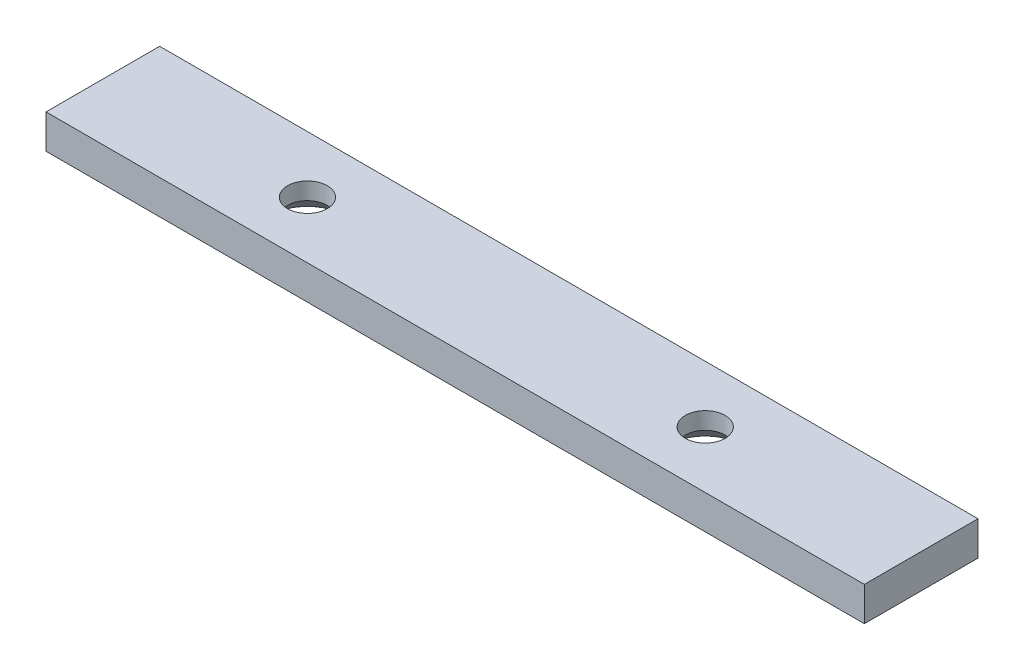
SolidWorks part; units mm, degrees
ref_plane "Front Plane" through (0, 0, 0) normal (0, 0, 1) x (1, 0, 0)
ref_plane "Top Plane" through (0, 0, 0) normal (0, 1, 0) x (1, 0, 0)
ref_plane "Right Plane" through (0, 0, 0) normal (1, 0, 0) x (0, 0, -1)
sketch "Sketch2" plane through (0, 0, 0) normal (0, 1, 0) x (1, 0, 0)
  line L1 (-72, 10) -> (72, 10)
  line L2 (-72, 10) -> (-72, -10)
  line L3 (-72, -10) -> (72, -10)
  line L4 (72, 10) -> (72, -10)
  line L5 (-72, 10) -> (72, -10) construction
  line L6 (-72, -10) -> (72, 10) construction
  point P0 (0, 0)
  dimension "D1" = 20
  dimension "D2" = 144
extrude "Boss-Extrude1" add sketch "Sketch2" along normal blind 6
hole_wizard "CSK for M2 Flat Head Machine Screw1" positions "3DSketch1" profile "Sketch3" countersink size "M2" standard "ANSI Metric" end condition up to next
sketch3d "3DSketch1"
  line L0 (72, 0, 10) -> (72, 0, -10) construction
  line L1 (-72, 0, 10) -> (72, 0, 10) construction
  point P0 (34, 0, 0)
  dimension "D1" = 38
  dimension "D2" = 10
sketch "Sketch3" plane through (34, 0, 0) normal (1, 0, 0) x (0, 0, -1)
  line L0 (0, 0) -> (0, 6)
  line L1 (0, 6) -> (3.5, 6)
  line L2 (3.5, 6) -> (3.5, 3)
  line L3 (3.5, 3) -> (6.5, 0)
  line L5 (6.5, 0) -> (0, 0)
  line L6 (-3.5, 3) -> (-6.5, 0) construction
  line L11 (0, -6.35) -> (0, 107.95) construction
  dimension "Thru Hole Dia." = 7
  dimension "Thru Hole Depth" = 6
  dimension "Near C'Sink Dia." = 13
  dimension "Near C'Sink Angle" = 90
pattern_linear "LPattern1" count 2 spacing 70 along (-1, 0, 0) of "CSK for M2 Flat Head Machine Screw1"
